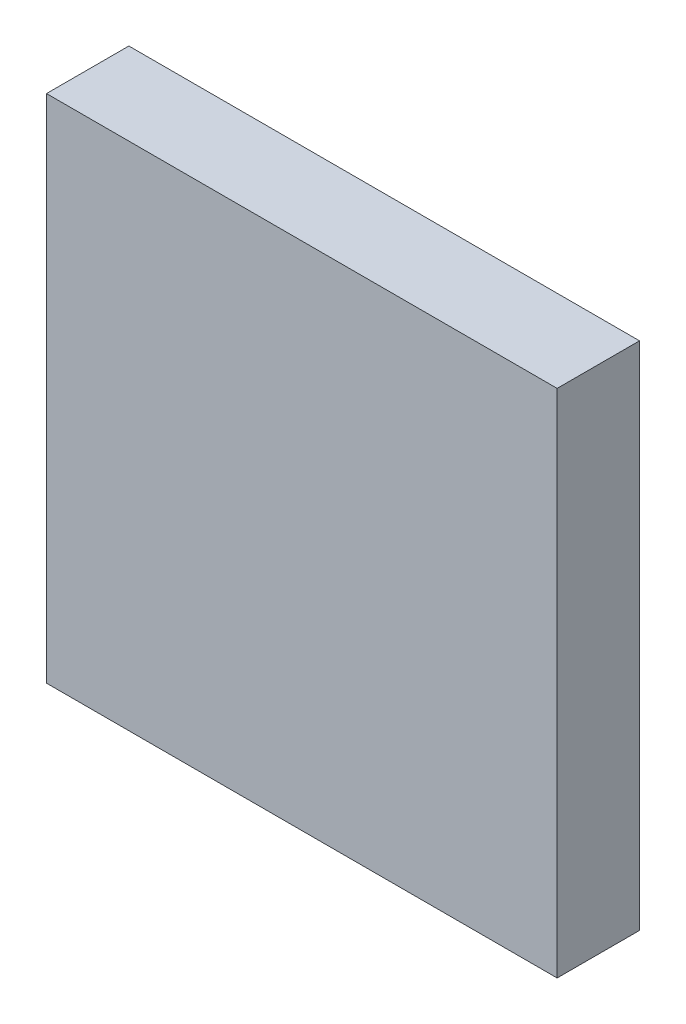
SolidWorks part; units mm, degrees
ref_plane "Спереди" through (0, 0, 0) normal (0, 0, 1) x (1, 0, 0)
ref_plane "Сверху" through (0, 0, 0) normal (0, 1, 0) x (1, 0, 0)
ref_plane "Справа" through (0, 0, 0) normal (1, 0, 0) x (0, 0, -1)
sketch "Эскиз5" plane through (0, 0, 0) normal (0, 0, 1) x (1, 0, 0)
  line L1 (-31, -31) -> (31, -31)
  line L2 (-31, -31) -> (-31, 31)
  line L3 (-31, 31) -> (31, 31)
  line L4 (31, -31) -> (31, 31)
  line L5 (-31, -31) -> (31, 31) construction
  line L6 (-31, 31) -> (31, -31) construction
  point P0 (0, 0)
extrude "Бобышка-Вытянуть2" add sketch "Эскиз5" along normal blind 10 contours L2 L3 L4 L1
sketch "Эскиз13" plane through (0, 0, 10) normal (0, 0, 1) x (1, 0, 0)
  line L0 (-8.5, 3.8388) -> (-8.5, -2.9703)
  line L1 (8.5, -2.9278) -> (8.5, 3.8388)
  spline S0 degree 3 poles (-3.7602, -6.2881) (-4.1456, -5.7125) (-4.7609, -5.3316) (-5.448, -5.2431) knots 0 0 0 0 0.333333 0.333333 0.333333 0.333333
  spline S1 degree 3 poles (-5.448, -5.2431) (-6.135, -5.1547) (-6.8268, -5.3675) (-7.3454, -5.8267) knots 0.333333 0.333333 0.333333 0.333333 1 1 1 1
  spline S2 degree 3 poles (-8.2703, 4.2595) (-8.4134, 4.1675) (-8.5, 4.009) (-8.5, 3.8388) knots 0 0 0 0 1 1 1 1
  spline S3 degree 3 poles (8.2703, 4.2595) (3.2319, 7.4966) (-3.2319, 7.4966) (-8.2703, 4.2595) knots 0 0 0 0 1 1 1 1
  spline S4 degree 3 poles (8.5, 3.8388) (8.5, 4.009) (8.4134, 4.1675) (8.2703, 4.2595) knots 0 0 0 0 1 1 1 1
  spline S5 degree 3 poles (-8.9672, -4.0581) (-8.6689, -3.7749) (-8.5, -3.3816) (-8.5, -2.9703) knots 0 0 0 0 1 1 1 1
  spline S6 degree 3 poles (-8.9672, -4.0581) (-9.4419, -4.5088) (-9.4678, -5.2568) (-9.0253, -5.7393) knots 0 0 0 0 0.333333 0.333333 0.333333 0.333333
  spline S7 degree 3 poles (-9.0253, -5.7393) (-8.5829, -6.2218) (-7.8355, -6.2607) (-7.3454, -5.8267) knots 0.333333 0.333333 0.333333 0.333333 1 1 1 1
  spline S8 degree 3 poles (8.5, -2.9278) (8.5, -3.3579) (8.6732, -3.77) (8.9805, -4.0709) knots 0 0 0 0 1 1 1 1
  spline S9 degree 3 poles (7.6987, -6.0438) (6.4648, -5.5547) (5.0779, -5.6352) (3.9089, -6.2639) knots 0 0 0 0 1 1 1 1
  spline S10 degree 3 poles (7.6987, -6.0438) (8.2299, -6.2544) (8.8358, -6.0612) (9.1472, -5.5821) knots 0 0 0 0 0.333333 0.333333 0.333333 0.333333
  spline S11 degree 3 poles (9.1472, -5.5821) (9.4585, -5.1029) (9.3888, -4.4707) (8.9805, -4.0709) knots 0.333333 0.333333 0.333333 0.333333 1 1 1 1
  spline S12 degree 3 poles (3.1792, -6.3186) (1.2825, -5.6394) (-0.8063, -5.741) (-2.6281, -6.6012) knots 0 0 0 0 1 1 1 1
  spline S13 degree 3 poles (-3.7602, -6.2881) (-3.5123, -6.6582) (-3.0309, -6.7914) (-2.6281, -6.6012) knots 0 0 0 0 1 1 1 1
  spline S14 degree 3 poles (3.1792, -6.3186) (3.4192, -6.4045) (3.6844, -6.3847) (3.9089, -6.2639) knots 0 0 0 0 1 1 1 1
sketch "Эскиз15" plane through (0, 0, 10) normal (0, 0, 1) x (1, 0, 0)
  line L0 (-8.5, 3.8389) -> (-8.5, -2.9702)
  line L1 (8.5, -2.9277) -> (8.5, 3.8389)
  line L2 (-12.5, -12.5) -> (12.5, -12.5)
  line L3 (12.5, -12.5) -> (12.5, 12.5)
  line L4 (12.5, 12.5) -> (-12.5, 12.5)
  line L5 (-12.5, 12.5) -> (-12.5, -12.5)
  spline S0 degree 3 poles (8, 2.6874) (8, 2.9636) (7.7761, 3.1874) (7.5, 3.1874) knots 0 0 0 0 0.2 0.2 0.2 0.2
  spline S1 degree 3 poles (7.5, 3.1874) (7.2239, 3.1874) (7, 2.9636) (7, 2.6874) knots 0.2 0.2 0.2 0.2 0.4 0.4 0.4 0.4
  spline S2 degree 3 poles (7, 2.6874) (7, 2.4113) (7.2239, 2.1874) (7.5, 2.1874) knots 0.4 0.4 0.4 0.4 0.6 0.6 0.6 0.6
  spline S3 degree 3 poles (7.5, 2.1874) (7.7761, 2.1874) (8, 2.4113) (8, 2.6874) knots 0.6 0.6 0.6 0.6 1 1 1 1
  spline S4 degree 3 poles (-4.6079, 1.1218) (-4.6079, 1.6188) (-5.0108, 2.0218) (-5.5079, 2.0218) knots 0 0 0 0 0.2 0.2 0.2 0.2
  spline S5 degree 3 poles (-5.5079, 2.0218) (-6.0049, 2.0218) (-6.4079, 1.6188) (-6.4079, 1.1218) knots 0.2 0.2 0.2 0.2 0.4 0.4 0.4 0.4
  spline S6 degree 3 poles (-6.4079, 1.1218) (-6.4079, 0.6247) (-6.0049, 0.2218) (-5.5079, 0.2218) knots 0.4 0.4 0.4 0.4 0.6 0.6 0.6 0.6
  spline S7 degree 3 poles (-5.5079, 0.2218) (-5.0108, 0.2218) (-4.6079, 0.6247) (-4.6079, 1.1218) knots 0.6 0.6 0.6 0.6 1 1 1 1
  spline S8 degree 3 poles (7.0549, -0.2908) (7.0549, 0.2063) (6.652, 0.6092) (6.1549, 0.6092) knots 0 0 0 0 0.2 0.2 0.2 0.2
  spline S9 degree 3 poles (6.1549, 0.6092) (5.6579, 0.6092) (5.2549, 0.2063) (5.2549, -0.2908) knots 0.2 0.2 0.2 0.2 0.4 0.4 0.4 0.4
  spline S10 degree 3 poles (5.2549, -0.2908) (5.2549, -0.7878) (5.6579, -1.1908) (6.1549, -1.1908) knots 0.4 0.4 0.4 0.4 0.6 0.6 0.6 0.6
  spline S11 degree 3 poles (6.1549, -1.1908) (6.652, -1.1908) (7.0549, -0.7878) (7.0549, -0.2908) knots 0.6 0.6 0.6 0.6 1 1 1 1
  spline S12 degree 3 poles (-7, 2.6874) (-7, 2.9636) (-7.2239, 3.1874) (-7.5, 3.1874) knots 0 0 0 0 0.2 0.2 0.2 0.2
  spline S13 degree 3 poles (-7.5, 3.1874) (-7.7761, 3.1874) (-8, 2.9636) (-8, 2.6874) knots 0.2 0.2 0.2 0.2 0.4 0.4 0.4 0.4
  spline S14 degree 3 poles (-8, 2.6874) (-8, 2.4113) (-7.7761, 2.1874) (-7.5, 2.1874) knots 0.4 0.4 0.4 0.4 0.6 0.6 0.6 0.6
  spline S15 degree 3 poles (-7.5, 2.1874) (-7.2239, 2.1874) (-7, 2.4113) (-7, 2.6874) knots 0.6 0.6 0.6 0.6 1 1 1 1
  spline S16 degree 3 poles (-7.5909, -4.9282) (-7.5909, -4.6244) (-7.8371, -4.3782) (-8.1409, -4.3782) knots 0 0 0 0 0.2 0.2 0.2 0.2
  spline S17 degree 3 poles (-8.1409, -4.3782) (-8.4447, -4.3782) (-8.6909, -4.6244) (-8.6909, -4.9282) knots 0.2 0.2 0.2 0.2 0.4 0.4 0.4 0.4
  spline S18 degree 3 poles (-8.6909, -4.9282) (-8.6909, -5.2319) (-8.4447, -5.4782) (-8.1409, -5.4782) knots 0.4 0.4 0.4 0.4 0.6 0.6 0.6 0.6
  spline S19 degree 3 poles (-8.1409, -5.4782) (-7.8371, -5.4782) (-7.5909, -5.2319) (-7.5909, -4.9282) knots 0.6 0.6 0.6 0.6 1 1 1 1
  spline S20 degree 3 poles (8.6909, -4.9282) (8.6909, -4.6244) (8.4447, -4.3782) (8.1409, -4.3782) knots 0 0 0 0 0.2 0.2 0.2 0.2
  spline S21 degree 3 poles (8.1409, -4.3782) (7.8371, -4.3782) (7.5909, -4.6244) (7.5909, -4.9282) knots 0.2 0.2 0.2 0.2 0.4 0.4 0.4 0.4
  spline S22 degree 3 poles (7.5909, -4.9282) (7.5909, -5.2319) (7.8371, -5.4782) (8.1409, -5.4782) knots 0.4 0.4 0.4 0.4 0.6 0.6 0.6 0.6
  spline S23 degree 3 poles (8.1409, -5.4782) (8.4447, -5.4782) (8.6909, -5.2319) (8.6909, -4.9282) knots 0.6 0.6 0.6 0.6 1 1 1 1
  spline S24 degree 3 poles (3.9826, -5.4712) (3.9826, -5.195) (3.7587, -4.9712) (3.4826, -4.9712) knots 0 0 0 0 0.2 0.2 0.2 0.2
  spline S25 degree 3 poles (3.4826, -4.9712) (3.2064, -4.9712) (2.9826, -5.195) (2.9826, -5.4712) knots 0.2 0.2 0.2 0.2 0.4 0.4 0.4 0.4
  spline S26 degree 3 poles (2.9826, -5.4712) (2.9826, -5.7473) (3.2064, -5.9712) (3.4826, -5.9712) knots 0.4 0.4 0.4 0.4 0.6 0.6 0.6 0.6
  spline S27 degree 3 poles (3.4826, -5.9712) (3.7587, -5.9712) (3.9826, -5.7473) (3.9826, -5.4712) knots 0.6 0.6 0.6 0.6 1 1 1 1
  spline S28 degree 3 poles (-2.5123, -5.7872) (-2.5123, -5.5111) (-2.7362, -5.2872) (-3.0123, -5.2872) knots 0 0 0 0 0.2 0.2 0.2 0.2
  spline S29 degree 3 poles (-3.0123, -5.2872) (-3.2885, -5.2872) (-3.5123, -5.5111) (-3.5123, -5.7872) knots 0.2 0.2 0.2 0.2 0.4 0.4 0.4 0.4
  spline S30 degree 3 poles (-3.5123, -5.7872) (-3.5123, -6.0634) (-3.2885, -6.2872) (-3.0123, -6.2872) knots 0.4 0.4 0.4 0.4 0.6 0.6 0.6 0.6
  spline S31 degree 3 poles (-3.0123, -6.2872) (-2.7362, -6.2872) (-2.5123, -6.0634) (-2.5123, -5.7872) knots 0.6 0.6 0.6 0.6 1 1 1 1
  spline S32 degree 3 poles (6.6049, -0.2908) (6.6049, -0.0422) (6.4034, 0.1592) (6.1549, 0.1592) knots 0 0 0 0 0.2 0.2 0.2 0.2
  spline S33 degree 3 poles (6.1549, 0.1592) (5.9064, 0.1592) (5.7049, -0.0422) (5.7049, -0.2908) knots 0.2 0.2 0.2 0.2 0.4 0.4 0.4 0.4
  spline S34 degree 3 poles (5.7049, -0.2908) (5.7049, -0.5393) (5.9064, -0.7408) (6.1549, -0.7408) knots 0.4 0.4 0.4 0.4 0.6 0.6 0.6 0.6
  spline S35 degree 3 poles (6.1549, -0.7408) (6.4034, -0.7408) (6.6049, -0.5393) (6.6049, -0.2908) knots 0.6 0.6 0.6 0.6 1 1 1 1
  spline S36 degree 3 poles (-5.0579, 1.1218) (-5.0579, 1.3703) (-5.2594, 1.5718) (-5.5079, 1.5718) knots 0 0 0 0 0.2 0.2 0.2 0.2
  spline S37 degree 3 poles (-5.5079, 1.5718) (-5.7564, 1.5718) (-5.9579, 1.3703) (-5.9579, 1.1218) knots 0.2 0.2 0.2 0.2 0.4 0.4 0.4 0.4
  spline S38 degree 3 poles (-5.9579, 1.1218) (-5.9579, 0.8733) (-5.7564, 0.6718) (-5.5079, 0.6718) knots 0.4 0.4 0.4 0.4 0.6 0.6 0.6 0.6
  spline S39 degree 3 poles (-5.5079, 0.6718) (-5.2594, 0.6718) (-5.0579, 0.8733) (-5.0579, 1.1218) knots 0.6 0.6 0.6 0.6 1 1 1 1
  spline S40 degree 3 poles (5.7898, -5.6368) (5.8728, -5.6949) (5.9715, -5.7264) (6.0728, -5.7271) knots 0 0 0 0 1 1 1 1
  spline S41 degree 3 poles (-5.4083, -5.2485) (-5.2964, -5.2648) (-5.1822, -5.2427) (-5.0845, -5.1857) knots 0 0 0 0 1 1 1 1
  spline S42 degree 3 poles (-3.7602, -6.288) (-4.1456, -5.7124) (-4.7609, -5.3315) (-5.448, -5.243) knots 0 0 0 0 0.333333 0.333333 0.333333 0.333333
  spline S43 degree 3 poles (-5.448, -5.243) (-6.135, -5.1546) (-6.8268, -5.3674) (-7.3454, -5.8266) knots 0.333333 0.333333 0.333333 0.333333 1 1 1 1
  spline S44 degree 3 poles (-8.2703, 4.2596) (-8.4134, 4.1676) (-8.5, 4.0091) (-8.5, 3.8389) knots 0 0 0 0 1 1 1 1
  spline S45 degree 3 poles (8.2703, 4.2596) (3.2319, 7.4967) (-3.2319, 7.4967) (-8.2703, 4.2596) knots 0 0 0 0 1 1 1 1
  spline S46 degree 3 poles (8.5, 3.8389) (8.5, 4.0091) (8.4134, 4.1676) (8.2703, 4.2596) knots 0 0 0 0 1 1 1 1
  spline S47 degree 3 poles (5.7898, -5.6368) (2.563, -3.3793) (-1.6818, -3.2032) (-5.0845, -5.1857) knots 0 0 0 0 1 1 1 1
  spline S48 degree 3 poles (-8.9672, -4.058) (-8.6689, -3.7748) (-8.5, -3.3815) (-8.5, -2.9702) knots 0 0 0 0 1 1 1 1
  spline S49 degree 3 poles (-8.9672, -4.058) (-9.4419, -4.5087) (-9.4678, -5.2567) (-9.0253, -5.7392) knots 0 0 0 0 0.333333 0.333333 0.333333 0.333333
  spline S50 degree 3 poles (-9.0253, -5.7392) (-8.5829, -6.2217) (-7.8355, -6.2606) (-7.3454, -5.8266) knots 0.333333 0.333333 0.333333 0.333333 1 1 1 1
  spline S51 degree 3 poles (8.5, -2.9277) (8.5, -3.3578) (8.6732, -3.7699) (8.9805, -4.0708) knots 0 0 0 0 1 1 1 1
  spline S52 degree 3 poles (7.6987, -6.0437) (6.4648, -5.5546) (5.0779, -5.6351) (3.9089, -6.2638) knots 0 0 0 0 1 1 1 1
  spline S53 degree 3 poles (7.6987, -6.0437) (8.2299, -6.2543) (8.8358, -6.0611) (9.1472, -5.582) knots 0 0 0 0 0.333333 0.333333 0.333333 0.333333
  spline S54 degree 3 poles (9.1472, -5.582) (9.4585, -5.1028) (9.3888, -4.4706) (8.9805, -4.0708) knots 0.333333 0.333333 0.333333 0.333333 1 1 1 1
  spline S55 degree 3 poles (3.1792, -6.3185) (1.2825, -5.6393) (-0.8063, -5.7409) (-2.6281, -6.6011) knots 0 0 0 0 1 1 1 1
  spline S56 degree 3 poles (-3.7602, -6.288) (-3.5123, -6.6581) (-3.0309, -6.7913) (-2.6281, -6.6011) knots 0 0 0 0 1 1 1 1
  spline S57 degree 3 poles (3.1792, -6.3185) (3.4192, -6.4044) (3.6844, -6.3846) (3.9089, -6.2638) knots 0 0 0 0 1 1 1 1
sketch "обнижение под перлаж" plane through (0, 0, 10) normal (0, 0, 1) x (1, 0, 0)
  ellipse E0 centre (0, -7.2674) end of major axis (6.1105, -7.2674) minor radius 3.5988
sketch "карман под съем моста" plane through (0, 0, 10) normal (0, 0, 1) x (1, 0, 0)
  line L0 (-13.7619, 0) -> (13.4181, 0) construction
  line L1 (-13.7619, 1) -> (13.4181, 1)
  line L2 (-13.7619, -1) -> (13.4181, -1)
  arc A0 (-13.7619, 1) -> (-13.7619, -1) centre (-13.7619, 0) ccw
  arc A1 (13.4181, -1) -> (13.4181, 1) centre (13.4181, 0) ccw
  point P3 (-0.1719, 0)
sketch "острова" plane through (0, 0, 10) normal (0, 0, 1) x (1, 0, 0)
  spline S0 degree 2 poles (-8.5, -2.0317) (-8.5, -2.5998) (-8.5, -2.9703) knots 0 0 0 1 1 1
  spline S1 degree 3 poles (-5.4691, 5.3435) (-5.4628, 5.5492) (-5.3311, 5.73) (-5.1372, 5.7991) knots 0 0 0 0 1 1 1 1
  spline S2 degree 3 poles (-8.3317, 4.2129) (-8.1698, 4.2866) (-7.9808, 4.2686) (-7.8357, 4.1657) knots 0 0 0 0 1 1 1 1
  spline S3 degree 3 poles (-8.3317, 4.2129) (-8.3126, 4.2298) (-8.2921, 4.2455) (-8.2703, 4.2595) knots 0 0 0 0 1 1 1 1
  spline S4 degree 3 poles (-8.0243, -2.5311) (-8.2907, -2.5182) (-8.5, -2.2984) (-8.5, -2.0317) knots 0 0 0 0 1 1 1 1
  spline S5 degree 3 poles (-8.0243, -2.5311) (-6.7965, -2.5908) (-5.8123, -3.5687) (-5.7445, -4.7961) knots 0 0 0 0 1 1 1 1
  spline S6 degree 3 poles (-5.3331, -5.2608) (-5.5614, -5.2201) (-5.7318, -5.0277) (-5.7445, -4.7961) knots 0 0 0 0 1 1 1 1
  spline S7 degree 3 poles (6.4277, -5.7438) (6.8591, -5.781) (7.2875, -5.8808) (7.6987, -6.0438) knots 0 0 0 0 1 1 1 1
  spline S8 degree 3 poles (6.962, -5.1523) (6.9912, -5.3061) (6.9468, -5.4647) (6.8418, -5.5808) knots 0 0 0 0 0.333333 0.333333 0.333333 0.333333
  spline S9 degree 3 poles (6.8418, -5.5808) (6.7369, -5.697) (6.5837, -5.7573) (6.4277, -5.7438) knots 0.333333 0.333333 0.333333 0.333333 1 1 1 1
  spline S10 degree 3 poles (6.962, -5.1523) (6.898, -4.8155) (6.9811, -4.4674) (7.1904, -4.1958) knots 0 0 0 0 0.333333 0.333333 0.333333 0.333333
  spline S11 degree 3 poles (7.1904, -4.1958) (7.3997, -3.9242) (7.7151, -3.7551) (8.0571, -3.7312) knots 0.333333 0.333333 0.333333 0.333333 1 1 1 1
  spline S12 degree 3 poles (8.5169, -3.1599) (8.5371, -3.2976) (8.499, -3.4375) (8.4117, -3.5459) knots 0 0 0 0 0.333333 0.333333 0.333333 0.333333
  spline S13 degree 3 poles (8.4117, -3.5459) (8.3245, -3.6543) (8.196, -3.7215) (8.0571, -3.7312) knots 0.333333 0.333333 0.333333 0.333333 1 1 1 1
  spline S14 degree 3 poles (8.9805, -4.0709) (8.729, -3.8247) (8.5673, -3.504) (8.5169, -3.1599) knots 0 0 0 0 1 1 1 1
  spline S15 degree 3 poles (8.2703, 4.2595) (8.2921, 4.2455) (8.3126, 4.2298) (8.3317, 4.2129) knots 0 0 0 0 1 1 1 1
  spline S16 degree 3 poles (7.8357, 4.1657) (7.9808, 4.2686) (8.1698, 4.2866) (8.3317, 4.2129) knots 0 0 0 0 1 1 1 1
  spline S17 degree 3 poles (7.8357, 4.1657) (7.3848, 3.8462) (6.7948, 3.8005) (6.3001, 4.0467) knots 0 0 0 0 0.333333 0.333333 0.333333 0.333333
  spline S18 degree 3 poles (6.3001, 4.0467) (5.8054, 4.2929) (5.4861, 4.7912) (5.4691, 5.3435) knots 0.333333 0.333333 0.333333 0.333333 1 1 1 1
  spline S19 degree 3 poles (5.1372, 5.7991) (5.3311, 5.73) (5.4628, 5.5492) (5.4691, 5.3435) knots 0 0 0 0 1 1 1 1
  spline S20 degree 3 poles (-8.2703, 4.2595) (-7.2743, 4.8994) (-6.2227, 5.4129) (-5.1372, 5.7991) knots 0 0 0 0 1 1 1 1
  spline S21 degree 3 poles (5.1372, 5.7991) (6.2227, 5.4129) (7.2744, 4.8994) (8.2703, 4.2595) knots 0 0 0 0 1 1 1 1
  spline S22 degree 3 poles (-7.3454, -5.8267) (-6.8268, -5.3675) (-6.135, -5.1547) (-5.448, -5.2431) knots 0 0 0 0 0.333333 0.333333 0.333333 0.333333
  spline S23 degree 3 poles (-5.448, -5.2431) (-5.4095, -5.2481) (-5.3711, -5.254) (-5.3331, -5.2608) knots 0.333333 0.333333 0.333333 0.333333 1 1 1 1
  spline S24 degree 3 poles (-5.4691, 5.3435) (-5.4861, 4.7912) (-5.8054, 4.2929) (-6.3001, 4.0467) knots 0 0 0 0 0.333333 0.333333 0.333333 0.333333
  spline S25 degree 3 poles (-6.3001, 4.0467) (-6.7948, 3.8005) (-7.3848, 3.8462) (-7.8357, 4.1657) knots 0.333333 0.333333 0.333333 0.333333 1 1 1 1
  spline S26 degree 3 poles (-8.5, -2.9703) (-8.5, -3.3816) (-8.6689, -3.7749) (-8.9672, -4.0581) knots 0 0 0 0 1 1 1 1
  spline S27 degree 3 poles (8.9805, -4.0709) (9.3888, -4.4707) (9.4585, -5.1029) (9.1472, -5.5821) knots 0 0 0 0 0.333333 0.333333 0.333333 0.333333
  spline S28 degree 3 poles (9.1472, -5.5821) (8.8358, -6.0612) (8.2299, -6.2544) (7.6987, -6.0438) knots 0.333333 0.333333 0.333333 0.333333 1 1 1 1
  spline S29 degree 3 poles (-7.3454, -5.8267) (-7.8355, -6.2607) (-8.5829, -6.2218) (-9.0253, -5.7393) knots 0 0 0 0 0.333333 0.333333 0.333333 0.333333
  spline S30 degree 3 poles (-9.0253, -5.7393) (-9.4678, -5.2568) (-9.4419, -4.5088) (-8.9672, -4.0581) knots 0.333333 0.333333 0.333333 0.333333 1 1 1 1
sketch "ПерлажЛицо" plane through (0, 0, 10) normal (0, 0, 1) x (1, 0, 0)
  circle A0 centre (-4.5709, -5.7941) radius 0.75
  circle A19 centre (-3.8009, -5.4102) radius 0.75
  circle A20 centre (-2.9989, -5.0985) radius 0.75
  circle A21 centre (-2.1719, -4.8614) radius 0.75
  circle A22 centre (-1.3266, -4.701) radius 0.75
  circle A23 centre (-0.4701, -4.6187) radius 0.75
  circle A24 centre (0.3903, -4.615) radius 0.75
  circle A25 centre (1.2474, -4.6901) radius 0.75
  circle A26 centre (2.094, -4.8433) radius 0.75
  circle A27 centre (2.9231, -5.0733) radius 0.75
  circle A28 centre (3.7276, -5.3782) radius 0.75
  circle A29 centre (4.5009, -5.7555) radius 0.75
  circle A30 centre (5.2364, -6.2019) radius 0.75
  point P27 (0, -14)
  point P30 (0, -14)
  point P45 (0, -14.9)
  dimension "D1" = 13
sketch "Эскиз16" plane through (0, 0, 10) normal (0, 0, 1) x (1, 0, 0)
  circle A0 centre (0, 0) radius 31
